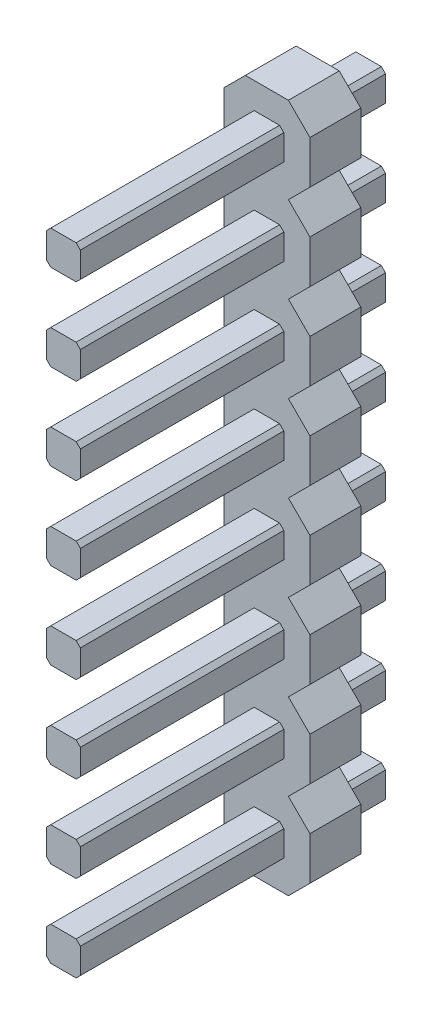
SolidWorks part; units mm, degrees
ref_plane "Plan de face" through (0, 0, 0) normal (0, 0, 1) x (1, 0, 0)
ref_plane "Plan de dessus" through (0, 0, 0) normal (0, 1, 0) x (1, 0, 0)
ref_plane "Plan de droite" through (0, 0, 0) normal (1, 0, 0) x (0, 0, -1)
sketch "Sketch1" plane through (0, 0, 0) normal (0, 0, 1) x (1, 0, 0)
  line L0 (-0.635, 10.16) -> (0.635, 10.16)
  line L1 (0.635, 10.16) -> (1.27, 9.525)
  line L2 (1.27, 9.525) -> (1.27, 8.255)
  line L3 (1.27, 8.255) -> (0.635, 7.62)
  line L4 (-0.635, 10.16) -> (-1.27, 9.525)
  line L5 (-1.27, 9.525) -> (-1.27, 8.255)
  line L6 (-1.27, 8.255) -> (-0.635, 7.62)
  line L7 (0.635, 7.62) -> (1.27, 6.985)
  line L8 (1.27, 6.985) -> (1.27, 5.715)
  line L9 (1.27, 5.715) -> (0.635, 5.08)
  line L10 (-0.635, 7.62) -> (-1.27, 6.985)
  line L11 (-1.27, 6.985) -> (-1.27, 5.715)
  line L12 (-1.27, 5.715) -> (-0.635, 5.08)
  line L13 (0.635, 5.08) -> (1.27, 4.445)
  line L14 (1.27, 4.445) -> (1.27, 3.175)
  line L15 (1.27, 3.175) -> (0.635, 2.54)
  line L16 (-0.635, 5.08) -> (-1.27, 4.445)
  line L17 (-1.27, 4.445) -> (-1.27, 3.175)
  line L18 (-1.27, 3.175) -> (-0.635, 2.54)
  line L19 (0.635, 2.54) -> (1.27, 1.905)
  line L20 (1.27, 1.905) -> (1.27, 0.635)
  line L21 (1.27, 0.635) -> (0.635, 0)
  line L22 (-0.635, 2.54) -> (-1.27, 1.905)
  line L23 (-1.27, 1.905) -> (-1.27, 0.635)
  line L24 (-1.27, 0.635) -> (-0.635, 0)
  line L25 (0.635, 0) -> (1.27, -0.635)
  line L26 (1.27, -0.635) -> (1.27, -1.905)
  line L27 (1.27, -1.905) -> (0.635, -2.54)
  line L28 (-0.635, 0) -> (-1.27, -0.635)
  line L29 (-1.27, -0.635) -> (-1.27, -1.905)
  line L30 (-1.27, -1.905) -> (-0.635, -2.54)
  line L31 (0.635, -2.54) -> (1.27, -3.175)
  line L32 (1.27, -3.175) -> (1.27, -4.445)
  line L33 (1.27, -4.445) -> (0.635, -5.08)
  line L34 (-0.635, -2.54) -> (-1.27, -3.175)
  line L35 (-1.27, -3.175) -> (-1.27, -4.445)
  line L36 (-1.27, -4.445) -> (-0.635, -5.08)
  line L37 (0.635, -5.08) -> (1.27, -5.715)
  line L38 (1.27, -5.715) -> (1.27, -6.985)
  line L39 (1.27, -6.985) -> (0.635, -7.62)
  line L40 (-0.635, -5.08) -> (-1.27, -5.715)
  line L41 (-1.27, -5.715) -> (-1.27, -6.985)
  line L42 (-1.27, -6.985) -> (-0.635, -7.62)
  line L43 (0.635, -7.62) -> (1.27, -8.255)
  line L44 (1.27, -8.255) -> (1.27, -9.525)
  line L45 (1.27, -9.525) -> (0.635, -10.16)
  line L46 (-0.635, -7.62) -> (-1.27, -8.255)
  line L47 (-1.27, -8.255) -> (-1.27, -9.525)
  line L48 (-1.27, -9.525) -> (-0.635, -10.16)
  line L49 (-0.635, -10.16) -> (0.635, -10.16)
  line L50 (-0.635, 7.62) -> (0.635, 7.62) construction
  line L51 (0, 10.16) -> (0, 7.62) construction
  point P0 (0, 8.89)
  point P1 (0, 8.89)
  point P54 (0, 8.89)
extrude "Boss-Extrude1" add sketch "Sketch1" along normal blind 1.5
sketch "Sketch2" plane through (0, 0, 1.5) normal (0, 0, 1) x (1, 0, 0)
  line L0 (-1.27, 8.89) -> (1.27, 8.89) construction
  line L1 (-1.27, 9.525) -> (-1.27, 8.255) construction
  line L2 (1.27, 8.255) -> (1.27, 9.525) construction
  line L3 (0.375, 9.39) -> (0.5, 9.265)
  line L4 (-0.375, 9.39) -> (0.375, 9.39)
  line L5 (-0.5, 9.265) -> (-0.5, 8.515)
  line L6 (-0.375, 8.39) -> (0.375, 8.39)
  line L7 (0.5, 9.265) -> (0.5, 8.515)
  line L8 (-0.5, 9.39) -> (0.5, 8.39) construction
  line L9 (-0.5, 8.39) -> (0.5, 9.39) construction
  line L10 (0.375, 8.39) -> (0.5, 8.515)
  line L11 (-0.5, 8.515) -> (-0.375, 8.39)
  line L12 (-0.5, 9.265) -> (-0.375, 9.39)
  line L13 (0.375, 6.85) -> (0.5, 6.725)
  line L14 (-0.375, 6.85) -> (0.375, 6.85)
  line L15 (-0.5, 6.725) -> (-0.5, 5.975)
  line L16 (-0.375, 5.85) -> (0.375, 5.85)
  line L17 (0.5, 6.725) -> (0.5, 5.975)
  line L18 (0.375, 5.85) -> (0.5, 5.975)
  line L19 (-0.5, 5.975) -> (-0.375, 5.85)
  line L20 (-0.5, 6.725) -> (-0.375, 6.85)
  line L21 (-1.27, 6.35) -> (1.27, 6.35) construction
  line L22 (-0.5, 6.85) -> (0.5, 5.85) construction
  line L23 (-0.5, 5.85) -> (0.5, 6.85) construction
  line L24 (0.375, 4.31) -> (0.5, 4.185)
  line L25 (-0.375, 4.31) -> (0.375, 4.31)
  line L26 (-0.5, 4.185) -> (-0.5, 3.435)
  line L27 (-0.375, 3.31) -> (0.375, 3.31)
  line L28 (0.5, 4.185) -> (0.5, 3.435)
  line L29 (0.375, 3.31) -> (0.5, 3.435)
  line L30 (-0.5, 3.435) -> (-0.375, 3.31)
  line L31 (-0.5, 4.185) -> (-0.375, 4.31)
  line L32 (-1.27, 3.81) -> (1.27, 3.81) construction
  line L33 (-0.5, 4.31) -> (0.5, 3.31) construction
  line L34 (-0.5, 3.31) -> (0.5, 4.31) construction
  line L35 (0.375, 1.77) -> (0.5, 1.645)
  line L36 (-0.375, 1.77) -> (0.375, 1.77)
  line L37 (-0.5, 1.645) -> (-0.5, 0.895)
  line L38 (-0.375, 0.77) -> (0.375, 0.77)
  line L39 (0.5, 1.645) -> (0.5, 0.895)
  line L40 (0.375, 0.77) -> (0.5, 0.895)
  line L41 (-0.5, 0.895) -> (-0.375, 0.77)
  line L42 (-0.5, 1.645) -> (-0.375, 1.77)
  line L43 (-1.27, 1.27) -> (1.27, 1.27) construction
  line L44 (-0.5, 1.77) -> (0.5, 0.77) construction
  line L45 (-0.5, 0.77) -> (0.5, 1.77) construction
  line L46 (0.375, -0.77) -> (0.5, -0.895)
  line L47 (-0.375, -0.77) -> (0.375, -0.77)
  line L48 (-0.5, -0.895) -> (-0.5, -1.645)
  line L49 (-0.375, -1.77) -> (0.375, -1.77)
  line L50 (0.5, -0.895) -> (0.5, -1.645)
  line L51 (0.375, -1.77) -> (0.5, -1.645)
  line L52 (-0.5, -1.645) -> (-0.375, -1.77)
  line L53 (-0.5, -0.895) -> (-0.375, -0.77)
  line L54 (-1.27, -1.27) -> (1.27, -1.27) construction
  line L55 (-0.5, -0.77) -> (0.5, -1.77) construction
  line L56 (-0.5, -1.77) -> (0.5, -0.77) construction
  line L57 (0.375, -3.31) -> (0.5, -3.435)
  line L58 (-0.375, -3.31) -> (0.375, -3.31)
  line L59 (-0.5, -3.435) -> (-0.5, -4.185)
  line L60 (-0.375, -4.31) -> (0.375, -4.31)
  line L61 (0.5, -3.435) -> (0.5, -4.185)
  line L62 (0.375, -4.31) -> (0.5, -4.185)
  line L63 (-0.5, -4.185) -> (-0.375, -4.31)
  line L64 (-0.5, -3.435) -> (-0.375, -3.31)
  line L65 (-1.27, -3.81) -> (1.27, -3.81) construction
  line L66 (-0.5, -3.31) -> (0.5, -4.31) construction
  line L67 (-0.5, -4.31) -> (0.5, -3.31) construction
  line L68 (0.375, -5.85) -> (0.5, -5.975)
  line L69 (-0.375, -5.85) -> (0.375, -5.85)
  line L70 (-0.5, -5.975) -> (-0.5, -6.725)
  line L71 (-0.375, -6.85) -> (0.375, -6.85)
  line L72 (0.5, -5.975) -> (0.5, -6.725)
  line L73 (0.375, -6.85) -> (0.5, -6.725)
  line L74 (-0.5, -6.725) -> (-0.375, -6.85)
  line L75 (-0.5, -5.975) -> (-0.375, -5.85)
  line L76 (-1.27, -6.35) -> (1.27, -6.35) construction
  line L77 (-0.5, -5.85) -> (0.5, -6.85) construction
  line L78 (-0.5, -6.85) -> (0.5, -5.85) construction
  line L79 (0.375, -8.39) -> (0.5, -8.515)
  line L80 (-0.375, -8.39) -> (0.375, -8.39)
  line L81 (-0.5, -8.515) -> (-0.5, -9.265)
  line L82 (-0.375, -9.39) -> (0.375, -9.39)
  line L83 (0.5, -8.515) -> (0.5, -9.265)
  line L84 (0.375, -9.39) -> (0.5, -9.265)
  line L85 (-0.5, -9.265) -> (-0.375, -9.39)
  line L86 (-0.5, -8.515) -> (-0.375, -8.39)
  line L87 (-1.27, -8.89) -> (1.27, -8.89) construction
  line L88 (-0.5, -8.39) -> (0.5, -9.39) construction
  line L89 (-0.5, -9.39) -> (0.5, -8.39) construction
  point P6 (0, 8.89)
  point P23 (0, 6.35)
  point P38 (0, 3.81)
  point P53 (0, 1.27)
  point P68 (0, -1.27)
  point P83 (0, -3.81)
  point P98 (0, -6.35)
  point P113 (0, -8.89)
  dimension "D1" = 1
  dimension "D2" = 1
  dimension "D3" = 8
extrude "Boss-Extrude2" add sketch "Sketch2" along normal blind 6 and the other way blind 3
